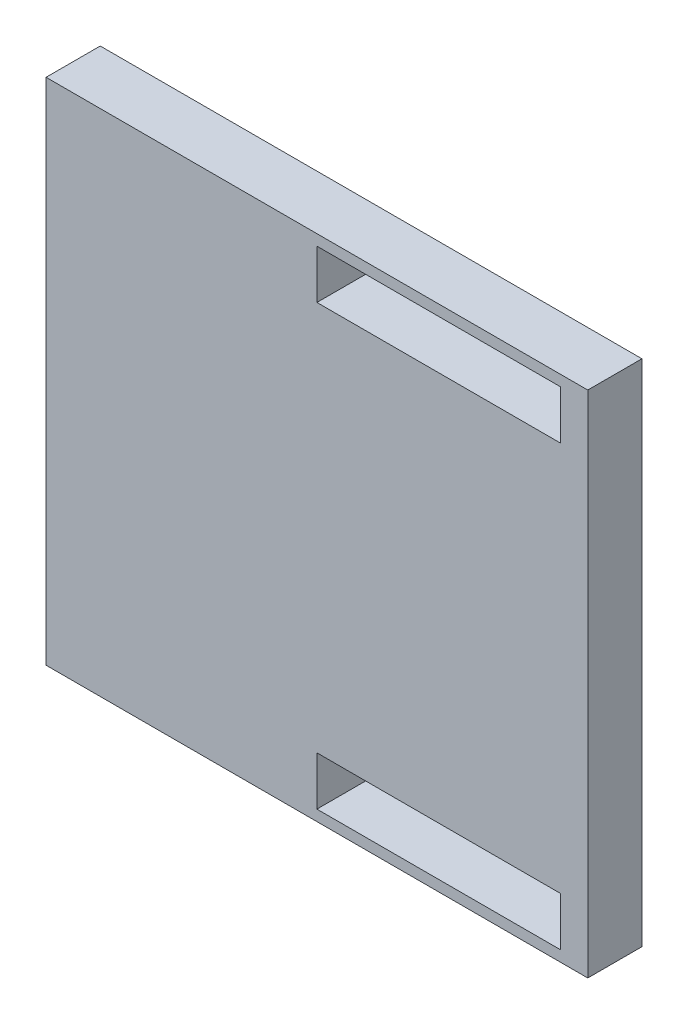
SolidWorks part; units mm, degrees
ref_plane "Front Plane" through (0, 0, 0) normal (0, 0, 1) x (1, 0, 0)
ref_plane "Top Plane" through (0, 0, 0) normal (0, 1, 0) x (1, 0, 0)
ref_plane "Right Plane" through (0, 0, 0) normal (1, 0, 0) x (0, 0, -1)
sketch "Sketch1" plane through (0, 0, 0) normal (0, 0, 1) x (1, 0, 0)
  line L1 (0, 0) -> (100, 0)
  line L2 (0, 0) -> (0, -94)
  line L3 (0, -94) -> (100, -94)
  line L4 (100, 0) -> (100, -94)
extrude "Boss-Extrude1" add sketch "Sketch1" along normal blind 10
sketch "Sketch2" plane through (0, 0, 0) normal (0, 0, -1) x (-1, 0, 0)
  line L0 (-100, -94) -> (-100, 0) construction
  line L1 (-95, -83) -> (-50, -83)
  line L2 (-95, -83) -> (-95, -92)
  line L3 (-95, -92) -> (-50, -92)
  line L4 (-50, -83) -> (-50, -92)
  line L5 (-95, -2) -> (-50, -2)
  line L6 (-95, -2) -> (-95, -11)
  line L7 (-95, -11) -> (-50, -11)
  line L8 (-50, -2) -> (-50, -11)
  line L9 (0, -94) -> (-100, -94) construction
  line L10 (-100, 0) -> (0, 0) construction
  dimension "D1" = 5
  dimension "D2" = 5
  dimension "D3" = 2
  dimension "D4" = 2
  dimension "D5" = 9
  dimension "D6" = 9
extrude "Cut-Extrude1" cut sketch "Sketch2" against normal blind 10
